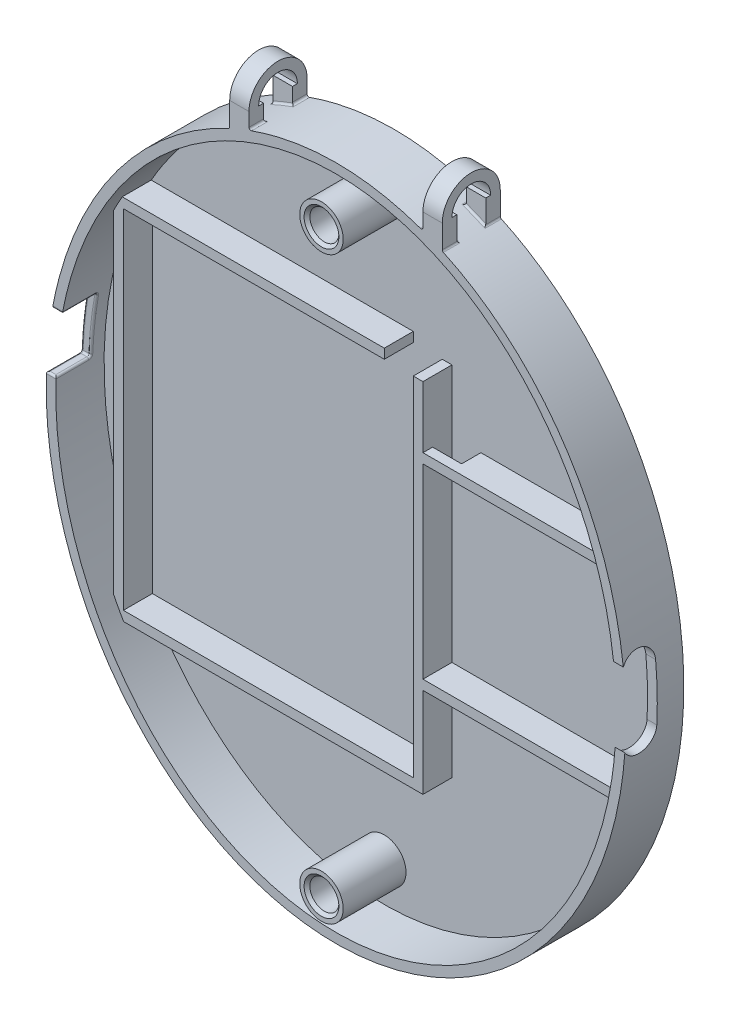
SolidWorks part; units mm, degrees
ref_plane "Front Plane" through (0, 0, 0) normal (0, 0, 1) x (1, 0, 0)
ref_plane "Top Plane" through (0, 0, 0) normal (0, 1, 0) x (1, 0, 0)
ref_plane "Right Plane" through (0, 0, 0) normal (1, 0, 0) x (0, 0, -1)
sketch "Sketch2" plane through (0, 0, 0) normal (0, 0, 1) x (1, 0, 0)
  ellipse E1 centre (0.0042, 0) end of major axis (0.0042, 35) minor radius 30
  dimension "D1" = 60
  dimension "D2" = 70
extrude "Base-Extrude" add sketch "Sketch2" along normal blind 6
sketch "Sketch4" plane through (0, 0, 6) normal (0, 0, 1) x (1, 0, 0)
  ellipse E0 centre (0, 0) end of major axis (0, -34) minor radius 29
  dimension "D1" = 68
  dimension "D2" = 58
extrude "Cut-Base" cut sketch "Sketch4" against normal offset from surface (5 mm away) 1 up to face at (0.0042, 35, 0)
ref_plane "Plane_USB" through (29.5, 0, 0) normal (1, 0, 0) x (0, 0, -1)
sketch "Sketch7" plane through (29.5, 0, 0) normal (1, 0, 0) x (0, 0, -1)
  line L0 (-4.5, 3.7522) -> (-4.5, -2.0478) construction
  line L1 (-2.75, 3.7522) -> (-2.75, -2.0478)
  line L2 (-6.25, 3.7522) -> (-6.25, -2.0478)
  line L5 (-6, 35) -> (-6, -35) construction
  line L6 (-1, 34) -> (-1, -34) construction
  arc A0 (-2.75, 3.7522) -> (-6.25, 3.7522) centre (-4.5, 3.7522) ccw
  arc A1 (-6.25, -2.0478) -> (-2.75, -2.0478) centre (-4.5, -2.0478) ccw
  point P2 (-4.5, 0.8522)
  dimension "D1" = 3.5
  dimension "D2" = 5.8
  dimension "D3" = 1.5
  dimension "D4" = 1.75
extrude "Cut-USB" cut sketch "Sketch7" against normal up to surface and the other way through all up to face at (0, -34, 1)
sketch "Sketch8" plane through (0, 0, 1) normal (0, 0, 1) x (1, 0, 0)
  circle A0 centre (0, -30) radius 2.25
  circle A1 centre (0, -30) radius 1.5
  ellipse E3 centre (0, 0) end of major axis (0, -34) minor radius 29 construction
  dimension "D1" = 4.5
  dimension "D2" = 30
  dimension "D3" = 3
extrude "Screw-Extrude1" add sketch "Sketch8" along normal blind 6.5 and the other way blind 0.5
chamfer "Chamfer1" distance 0.3 angle 45 1 edges at (1.5, -30, 7.5)
pattern_linear "LPattern1" count 2 spacing 60 along (0, 1, 0) of "Screw-Extrude1", "Chamfer1"
ref_plane "Plane_Cord" through (0, 35, 0) normal (0, 1, 0) x (1, 0, 0)
sketch "Sketch13" plane through (0, 35, 0) normal (0, 1, 0) x (1, 0, 0)
  line L0 (30.0042, 0) -> (-29.9958, 0) construction
  line L1 (-10.9958, -4.5) -> (-8.9958, -4.5)
  line L2 (-10.9958, -4.5) -> (-10.9958, -6)
  line L5 (-10.9958, -6) -> (-8.9958, -6)
  line L10 (-8.9958, -4.5) -> (-8.9958, -6)
  line L11 (-29.9958, -6) -> (29.8975, -6) construction
  line L12 (-10.9958, -1.5) -> (-8.9958, -1.5)
  line L13 (-10.9958, -1.5) -> (-10.9958, 0)
  line L14 (-10.9958, 0) -> (-8.9958, 0)
  line L15 (-8.9958, -1.5) -> (-8.9958, 0)
  line L16 (-29.9958, 0) -> (-29.9958, -6) construction
  dimension "D1" = 0
  dimension "D2" = 2
  dimension "D3" = 1.5
  dimension "D4" = 0
  dimension "D5" = 4.5
  dimension "D6" = 1.5
  dimension "D7" = 0
  dimension "D8" = 19
extrude "Boss-Extrude4" add sketch "Sketch13" along normal blind 0.08 and the other way blind 2.6
ref_plane "Plane_Cord2" through (-10.9958, 0, 0) normal (-1, 0, 0) x (0, 0, 1)
sketch "Sketch15" plane through (-10.9958, 0, 0) normal (-1, 0, 0) x (0, 0, 1)
  line L0 (0.0036, 35) -> (6, 35)
  line L1 (3.0016, 35) -> (-3.0016, 35) construction
  line L2 (6, 32.5623) -> (6, 35.08) construction
  arc A0 (0.0036, 35) -> (6, 35) centre (3.0018, 35.1032) cw
  arc A1 (1.0044, 35) -> (4.9991, 35) centre (3.0018, 35.1032) cw
  dimension "D1" = 0
  dimension "D2" = 2
  dimension "D3" = 1
extrude "Boss-Extrude5" add sketch "Sketch15" against normal up to surface (2 mm away) up to face at (-8.9958, 34.2339, 0.75)
pattern_linear "LPattern2" count 2 spacing 20 along (1, 0, 0) of "Boss-Extrude5", "Boss-Extrude4"
ref_plane "PlaneBT" through (-30, 0, 0) normal (1, 0, 0) x (0, 0, -1)
sketch "Sketch16" plane through (-30, 0, 0) normal (1, 0, 0) x (0, 0, -1)
  line L1 (-6, 1.312) -> (-6, 7.312)
  line L2 (-6, 1.312) -> (-2.4, 1.312)
  line L3 (-2.4, 1.312) -> (-2.4, 7.312)
  line L4 (-6, 7.312) -> (-2.4, 7.312)
  line L7 (-6, 32.5623) -> (-6, -35) construction
  dimension "D1" = 3.6
  dimension "D2" = 6
  dimension "D3" = 0
  dimension "D4" = 3.6
extrude "Cut-BT" cut sketch "Sketch16" along normal up to next
fillet "Fillet2" radius 0.2 22 edges at (-29.9747, 1.312, 4.2) (-28.9784, 1.312, 4.2) (-29.4765, 1.312, 2.4) (-29.4765, 1.312, 6) (-29.3338, 7.312, 4.2) (-28.8276, 7.312, 6) (-28.8276, 7.312, 2.4) (-28.3214, 7.312, 4.2) (-29.7655, 4.3281, 2.4) (-28.764, 4.3291, 2.4) (9.0042, 33.3879, 5.25) (10.0105, 32.9957, 4.5) (11.0042, 32.5623, 5.25) (10.0105, 32.9957, 1.5) (9.0042, 33.3879, 0.75) (11.0042, 32.5623, 0.75) (-8.9958, 33.3879, 5.25) (-8.9958, 33.3879, 0.75) (-10.002, 32.9957, 4.5) (-10.9958, 32.5623, 5.25) (-10.9958, 32.5623, 0.75) (-10.002, 32.9957, 1.5)
sketch "Sketch17" plane through (0, 0, 1) normal (0, 0, 1) x (1, 0, 0)
  line L1 (-25, 18.8738) -> (7, 18.8738)
  line L2 (-25, 18.8738) -> (-25, -19.1262)
  line L3 (-25, -19.1262) -> (7, -19.1262)
  line L4 (7, 18.8738) -> (7, -19.1262)
  line L6 (-24, 17.8738) -> (6, 17.8738)
  line L7 (-24, 17.8738) -> (-24, -18.1262)
  line L8 (-24, -18.1262) -> (6, -18.1262)
  line L9 (6, 17.8738) -> (6, -18.1262)
  ellipse E3 centre (0, 0) end of major axis (0, -34) minor radius 29 construction
  dimension "D1" = 38
  dimension "D2" = 32
  dimension "D3" = 25
  dimension "D4" = 1
  dimension "D5" = 1
  dimension "D6" = 1
  dimension "D7" = 1
extrude "BatteryHolder" add sketch "Sketch17" along normal blind 3
sketch "Sketch20" plane through (0, 18.8738, 0) normal (0, 1, 0) x (1, 0, 0)
  line L0 (7, -4) -> (7, -1) construction
  line L1 (7, -4) -> (3, -4)
  line L2 (7, -4) -> (7, -1)
  line L3 (7, -1) -> (3, -1)
  line L4 (3, -4) -> (3, -1)
  line L5 (7, -1) -> (-24.1215, -1) construction
  dimension "D1" = 3
  dimension "D2" = 4
extrude "Battery_Cable2" cut sketch "Sketch20" against normal up to surface (1 mm away) up to face at (-9, 17.8738, 2.5)
sketch "Sketch22" plane through (0, 0, 1) normal (0, 0, 1) x (1, 0, 0)
  line L0 (7, -19.1262) -> (7, 17.8738) construction
  line L1 (7, 11.5022) -> (27.5818, 11.5022)
  line L2 (7, 11.5022) -> (7, 10.5022)
  line L3 (7, 10.5022) -> (27.5818, 10.5022)
  line L4 (27.5818, 11.5022) -> (27.5818, 10.5022)
  line L5 (7, -8.7978) -> (28, -8.7978)
  line L6 (7, -8.7978) -> (7, -9.7978)
  line L7 (7, -9.7978) -> (28, -9.7978)
  line L8 (28, -8.7978) -> (28, -9.7978)
  line L9 (7, -19.1262) -> (7, 17.8738) construction
  line L10 (28.8185, -3.7978) -> (29.8271, -3.7978) construction
  line L13 (29.6312, 5.5022) -> (28.6178, 5.5022) construction
  ellipse E0 centre (0, 0) end of major axis (0, -34) minor radius 29 construction
  dimension "D1" = 5
  dimension "D2" = 20.5818
  dimension "D3" = 21
  dimension "D4" = 0
  dimension "D5" = 5
  dimension "D6" = 1
  dimension "D7" = 1
extrude "Boss-Extrude9" add sketch "Sketch22" along normal blind 3
sketch "Sketch23" plane through (0, 10.5022, 0) normal (0, -1, 0) x (1, 0, 0)
  line L0 (7, 1) -> (27.5818, 1) construction
  line L1 (7, 3) -> (10, 3)
  line L2 (7, 3) -> (7, 1)
  line L3 (7, 1) -> (10, 1)
  line L4 (10, 3) -> (10, 1)
  line L5 (7, 4) -> (7, 1) construction
  dimension "D1" = 0
  dimension "D2" = 2
  dimension "D3" = 3
  dimension "D4" = 0
extrude "Cut-Extrude6" cut sketch "Sketch23" against normal up to surface (1 mm away) up to face at (17.1451, 11.5022, 2.5)
